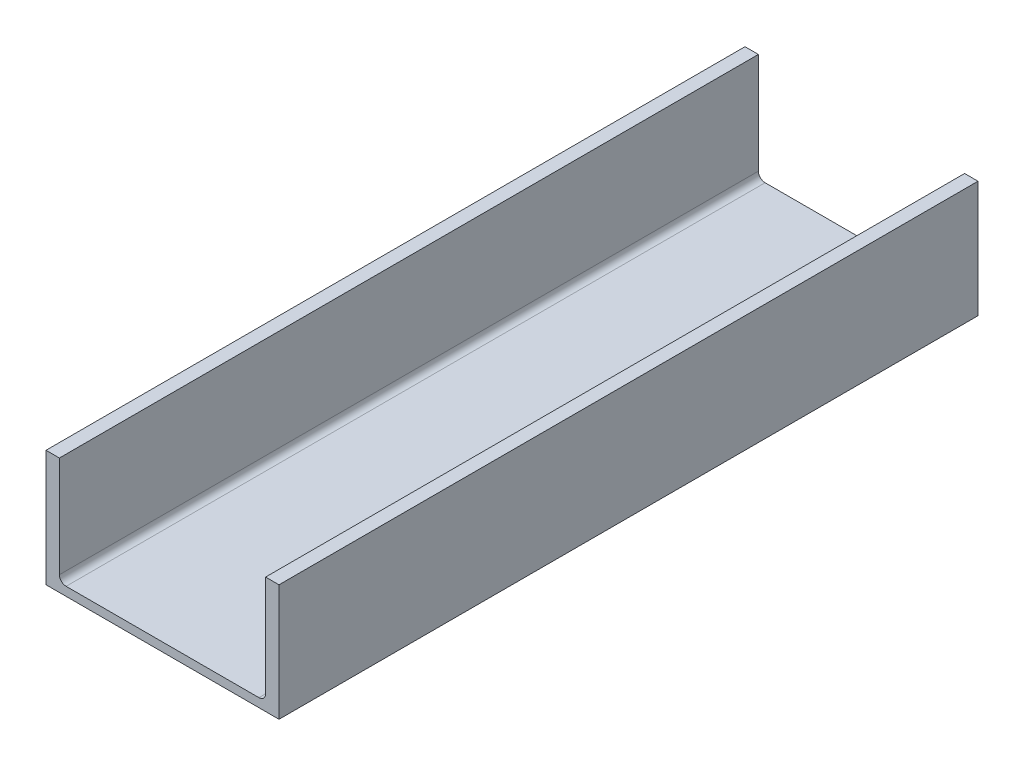
SolidWorks part; units mm, degrees
ref_plane "Front Plane" through (0, 0, 0) normal (0, 0, 1) x (1, 0, 0)
ref_plane "Top Plane" through (0, 0, 0) normal (0, 1, 0) x (1, 0, 0)
ref_plane "Right Plane" through (0, 0, 0) normal (1, 0, 0) x (0, 0, -1)
sketch "Sketch1" plane through (0, 0, 0) normal (0, 0, 1) x (1, 0, 0)
  line L0 (-50.8, 25.4) -> (-50.8, -25.4) construction
  line L1 (-50.8, -25.4) -> (50.8, -25.4) construction
  line L2 (50.8, -25.4) -> (50.8, 25.4) construction
  line L3 (44.958, -21.59) -> (-44.958, -21.59) construction
  line L4 (-44.958, -21.59) -> (-44.958, 25.4) construction
  line L6 (-44.958, 25.4) -> (-50.8, 25.4) construction
  line L7 (0, -25.4) -> (0, 0) construction
  line L8 (50.8, 25.4) -> (44.958, 25.4) construction
  line L9 (44.958, 25.4) -> (44.958, -21.59) construction
  line L10 (0, -21.59) -> (0, -25.4) construction
  point P4 (0, 0)
  point P11 (50.8, -21.59)
  dimension "Outside Height" = 50.8
  dimension "Outside Width" = 101.6
  dimension "Leg Thickness" = 5.842
  dimension "D1" = 25.4
  dimension "Inside Height" = 46.99
  dimension "Inside Width" = 89.916
  dimension "Base Thickness" = 3.81
sketch "Sketch2" plane through (0, 0, 0) normal (1, 0, 0) x (0, 0, -1)
  line L0 (152.4, 25.4) -> (-152.4, 25.4) construction
  line L1 (0, -21.59) -> (0, 25.4) construction
  point P0 (-76.2, 25.4)
  point P4 (0, 25.4)
  point P6 (76.2, 25.4)
  dimension "D1" = 76.2
  dimension "D2" = 76.2
  dimension "Length" = 304.8
sketch "Sketch3" plane through (0, 0, 0) normal (0, 0, 1) x (1, 0, 0)
  line L6 (-50.8, 25.4) -> (-50.8, -25.4)
  line L7 (-50.8, -25.4) -> (50.8, -25.4)
  line L8 (50.8, -25.4) -> (50.8, 25.4)
  line L9 (50.8, 25.4) -> (44.958, 25.4)
  line L10 (44.958, 25.4) -> (44.958, -21.59)
  line L11 (44.958, -21.59) -> (-44.958, -21.59)
  line L12 (-44.958, -21.59) -> (-44.958, 25.4)
  line L13 (-44.958, 25.4) -> (-50.8, 25.4)
extrude "Boss-Extrude1" add sketch "Sketch3" along normal mid plane 304.8
fillet "Fillet1" radius 2.921 2 edges at (44.958, -21.59, 0) (-44.958, -21.59, 0)
equation "\"D1@Boss-Extrude1\"=\"Length@Sketch2\""
equation "\"D2@Sketch2\"=\"D1@Sketch2\""
equation "\"D1@Sketch1\"=\"Outside Height@Sketch1\"/2"
equation "\"D1@Fillet1\"=\"Leg Thickness@Sketch1\"*.5"
